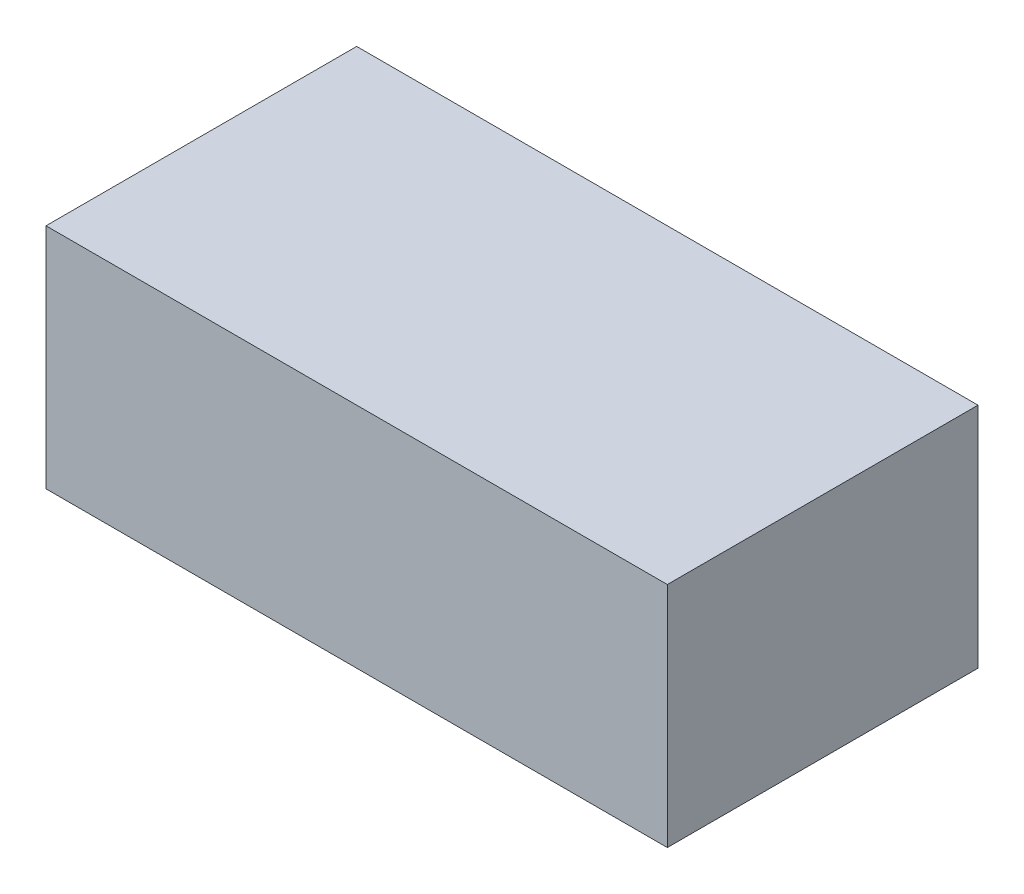
SolidWorks part; units mm, degrees
ref_plane "Front Plane" through (0, 0, 0) normal (0, 0, 1) x (1, 0, 0)
ref_plane "Top Plane" through (0, 0, 0) normal (0, 1, 0) x (1, 0, 0)
ref_plane "Right Plane" through (0, 0, 0) normal (1, 0, 0) x (0, 0, -1)
sketch "Sketch1" plane through (0, 0, 0) normal (0, 1, 0) x (1, 0, 0)
  line L1 (-19.6486, 10.016) -> (40.3514, 10.016)
  line L2 (-19.6486, 10.016) -> (-19.6486, -19.984)
  line L3 (-19.6486, -19.984) -> (40.3514, -19.984)
  line L4 (40.3514, 10.016) -> (40.3514, -19.984)
  dimension "D1" = 60
  dimension "D2" = 30
extrude "Boss-Extrude1" add sketch "Sketch1" along normal blind 22
